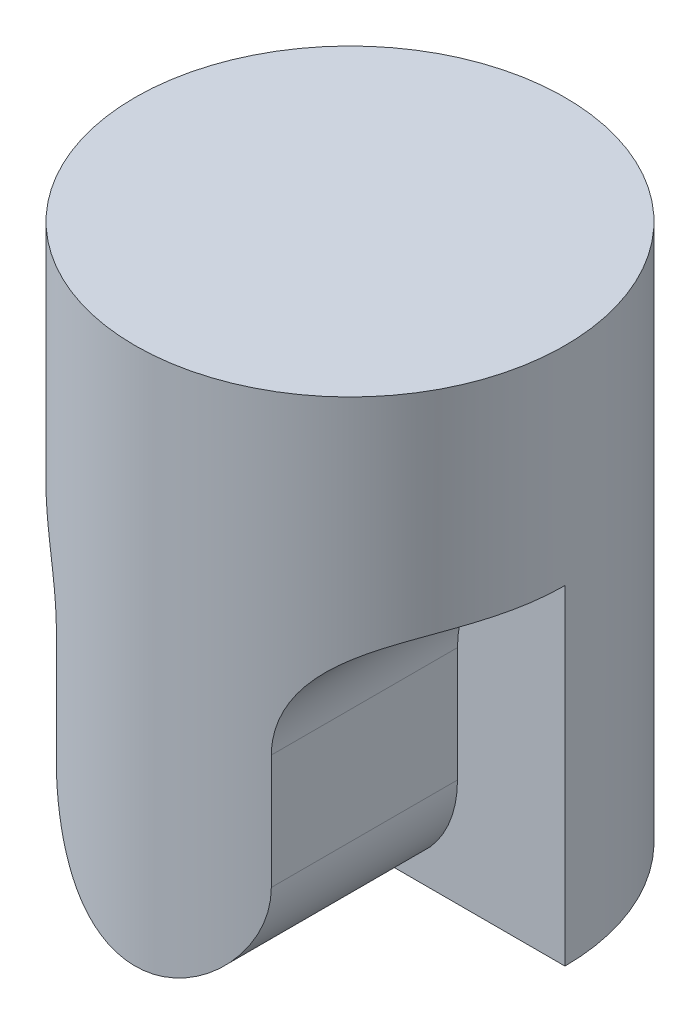
SolidWorks part; units mm, degrees
ref_plane "Front Plane" through (0, 0, 0) normal (0, 0, 1) x (1, 0, 0)
ref_plane "Top Plane" through (0, 0, 0) normal (0, 1, 0) x (1, 0, 0)
ref_plane "Right Plane" through (0, 0, 0) normal (1, 0, 0) x (0, 0, -1)
sketch "Sketch1" plane through (0, 0, 0) normal (0, 1, 0) x (1, 0, 0)
  circle A0 centre (0, 0) radius 19.05
extrude "Boss-Extrude1" add sketch "Sketch1" along normal blind 47.625
sketch "Sketch2" plane through (0, 0, 0) normal (0, 0, 1) x (1, 0, 0)
  line L0 (-19.05, -1.366) -> (19.05, -1.366)
  line L1 (19.05, -1.366) -> (19.05, 29.21)
  line L2 (9.525, 19.685) -> (9.525, 9.525)
  line L3 (-9.525, 9.525) -> (-9.525, 19.685)
  line L4 (-19.05, 29.21) -> (-19.05, -1.366)
  line L5 (-19.05, 0) -> (19.05, 0) construction
  arc A0 (19.05, 29.21) -> (9.525, 19.685) centre (19.05, 19.685) ccw
  arc A1 (-9.525, 9.525) -> (9.525, 9.525) centre (0, 9.525) ccw
  arc A2 (-9.525, 19.685) -> (-19.05, 29.21) centre (-19.05, 19.685) ccw
  dimension "D1" = 9.525
  dimension "D2" = 9.525
  dimension "D3" = 9.525
  dimension "D4" = 38.1
  dimension "D5" = 10.16
  dimension "D6" = 10.16
extrude "Cut-Extrude1" cut sketch "Sketch2" along normal through all
